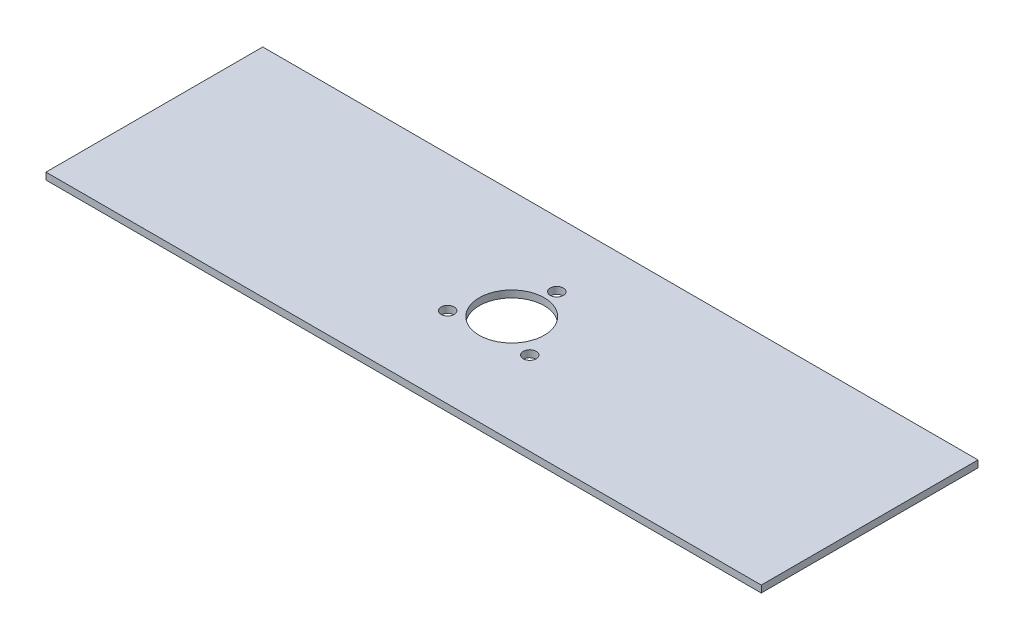
SolidWorks part; units mm, degrees
ref_plane "Front Plane" through (0, 0, 0) normal (0, 0, 1) x (1, 0, 0)
ref_plane "Top Plane" through (0, 0, 0) normal (0, 1, 0) x (1, 0, 0)
ref_plane "Right Plane" through (0, 0, 0) normal (1, 0, 0) x (0, 0, -1)
sketch "Sketch1" plane through (0, 0, 0) normal (0, 1, 0) x (1, 0, 0)
  line L1 (-91.9861, 41.8249) -> (73.0139, 41.8249)
  line L2 (-91.9861, 41.8249) -> (-91.9861, -8.1751)
  line L3 (-91.9861, -8.1751) -> (73.0139, -8.1751)
  line L4 (73.0139, 41.8249) -> (73.0139, -8.1751)
  dimension "D1" = 165
  dimension "D2" = 50
extrude "Boss-Extrude1" add sketch "Sketch1" along normal blind 1.6 contours L1 L4 L3 L2
sketch "Sketch2" plane through (0, 1.6, 0) normal (0, 1, 0) x (1, 0, 0)
  line L1 (72.807, -8.3796) -> (73.1633, 42.0294) construction
  line L3 (-8.9024, 16.0529) -> (-9.2079, 30.0061) construction
  line L4 (-8.7937, 16.2468) -> (-20.6918, 9.0256) construction
  line L5 (-8.6752, 16.0884) -> (2.775, 9.8077) construction
  dimension "D1" = 120
  dimension "D2" = 120
hole_wizard "Ø5.0mm Dowel Hole1" positions "Sketch3" profile "Sketch4" hole size "Ø5.0" standard "ANSI Metric" end condition through all
sketch "Sketch3" plane through (0, 1.6, 0) normal (0, 1, 0) x (1, 0, 0)
  point P0 (-9.4179, 16.695)
sketch "Sketch4" plane through (-9.4179, 1.6, -16.695) normal (1, 0, 0) x (0, 0, 1)
  line L0 (0, 0) -> (0, 1.6)
  line L1 (0, 1.6) -> (7.5, 1.6)
  line L2 (7.5, 1.6) -> (7.5, 0)
  line L5 (7.5, 0) -> (0, 0)
  line L11 (0, -6.35) -> (0, 107.95) construction
  dimension "Thru Hole Dia." = 15
  dimension "Thru Hole Depth" = 1.6
hole_wizard "Ø3.0mm Dowel Hole1" positions "Sketch5" profile "Sketch6" hole size "Ø3.0" standard "ANSI Metric" end condition through all
sketch "Sketch5" plane through (0, 1.6, 0) normal (0, 1, 0) x (1, 0, 0)
  point P0 (-9.1734, 26.8391)
sketch "Sketch6" plane through (-9.1734, 1.6, -26.8391) normal (1, 0, 0) x (0, 0, 1)
  line L0 (0, 0) -> (0, 1.6)
  line L1 (0, 1.6) -> (1.5, 1.6)
  line L2 (1.5, 1.6) -> (1.5, 0)
  line L5 (1.5, 0) -> (0, 0)
  line L11 (0, -6.35) -> (0, 107.95) construction
  dimension "Thru Hole Dia." = 3
  dimension "Thru Hole Depth" = 1.6
hole_wizard "Ø3.0mm Dowel Hole2" positions "Sketch7" profile "Sketch8" hole size "Ø3.0" standard "ANSI Metric" end condition through all
sketch "Sketch7" plane through (0, 1.6, 0) normal (0, 1, 0) x (1, 0, 0)
  point P0 (0.3596, 11.0729)
sketch "Sketch8" plane through (0.3596, 1.6, -11.0729) normal (1, 0, 0) x (0, 0, 1)
  line L0 (0, 0) -> (0, 1.6)
  line L1 (0, 1.6) -> (1.5, 1.6)
  line L2 (1.5, 1.6) -> (1.5, 0)
  line L5 (1.5, 0) -> (0, 0)
  line L11 (0, -6.35) -> (0, 107.95) construction
  dimension "Thru Hole Dia." = 3
  dimension "Thru Hole Depth" = 1.6
hole_wizard "Ø3.0mm Dowel Hole3" positions "Sketch9" profile "Sketch10" hole size "Ø3.0" standard "ANSI Metric" end condition through all
sketch "Sketch9" plane through (0, 1.6, 0) normal (0, 1, 0) x (1, 0, 0)
  point P0 (-17.9732, 10.4619)
sketch "Sketch10" plane through (-17.9732, 1.6, -10.4619) normal (1, 0, 0) x (0, 0, 1)
  line L0 (0, 0) -> (0, 1.6)
  line L1 (0, 1.6) -> (1.5, 1.6)
  line L2 (1.5, 1.6) -> (1.5, 0)
  line L5 (1.5, 0) -> (0, 0)
  line L11 (0, -6.35) -> (0, 107.95) construction
  dimension "Thru Hole Dia." = 3
  dimension "Thru Hole Depth" = 1.6
